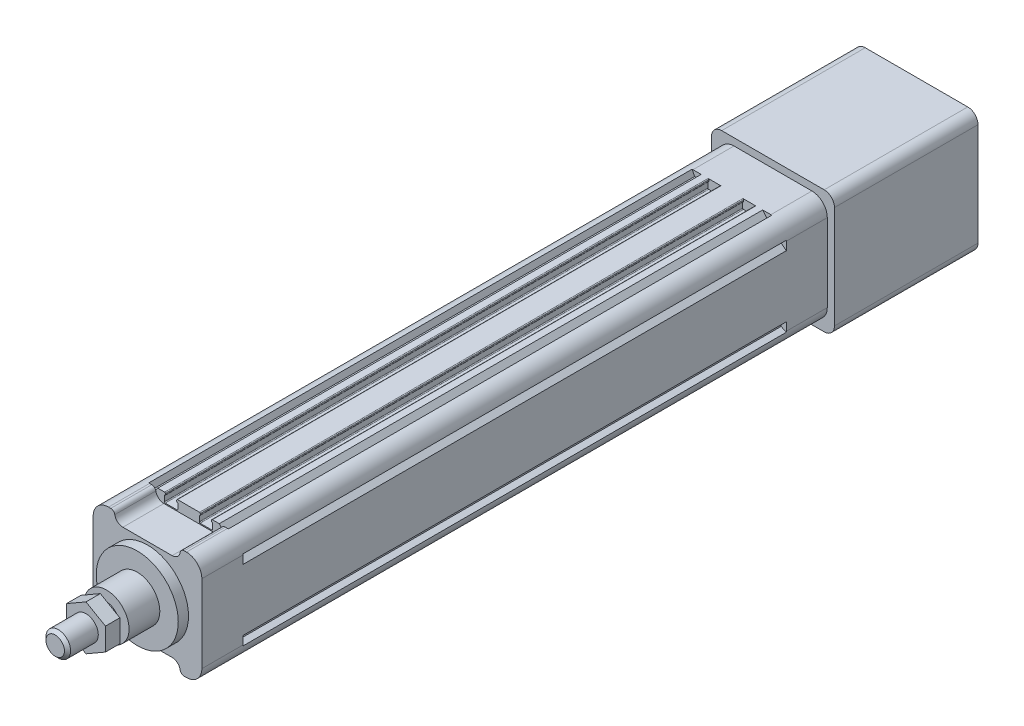
SolidWorks part; units mm, degrees
ref_plane "Front" through (0, 0, 0) normal (0, 0, 1) x (1, 0, 0)
ref_plane "Top" through (0, 0, 0) normal (0, 1, 0) x (1, 0, 0)
ref_plane "Right" through (0, 0, 0) normal (1, 0, 0) x (0, 0, -1)
sketch "草图1" plane through (0, 0, 0) normal (0, 0, 1) x (1, 0, 0)
  line L0 (19.7737, 3) -> (23.3, 3)
  line L1 (23.3, 3) -> (23.3, -3)
  line L2 (23.3, -3) -> (19.7737, -3)
  line L3 (-19.7737, -3) -> (-23.3, -3)
  line L4 (-23.3, -3) -> (-23.3, 3)
  line L5 (-23.3, 3) -> (-19.7737, 3)
  line L6 (-18.2, 24) -> (-19.4434, 26.4869)
  line L7 (-26.4869, 19.4434) -> (-24, 18.2)
  line L8 (-24, 18.2) -> (-24, 17.1)
  line L9 (-24, 17.1) -> (-26.5, 15)
  line L10 (-26.5, 15) -> (-26.5, -15)
  line L11 (-26.5, -15) -> (-24, -17.1)
  line L12 (-24, -17.1) -> (-24, -18.2)
  line L13 (-24, -18.2) -> (-26.4869, -19.4434)
  line L14 (-19.4434, -26.4869) -> (-18.2, -24)
  line L15 (-18.2, -24) -> (-17.1, -24)
  line L16 (-17.1, -24) -> (-15, -26.5)
  line L17 (-15, -26.5) -> (-11.65, -26.5)
  line L18 (-11.25, -26.1) -> (-11.25, -25.6)
  line L19 (-11.65, -25.2) -> (-11.75, -25.2)
  line L20 (-11.75, -25.2) -> (-11.75, -22.4)
  line L21 (-11.35, -22) -> (-5.65, -22)
  line L22 (-5.25, -22.4) -> (-5.25, -25.2)
  line L23 (-5.25, -25.2) -> (-5.35, -25.2)
  line L24 (-5.75, -25.6) -> (-5.75, -26.1)
  line L25 (-5.35, -26.5) -> (5.35, -26.5)
  line L26 (5.75, -26.1) -> (5.75, -25.6)
  line L27 (5.35, -25.2) -> (5.25, -25.2)
  line L28 (5.25, -25.2) -> (5.25, -22.4)
  line L29 (5.65, -22) -> (11.35, -22)
  line L30 (11.75, -22.4) -> (11.75, -25.2)
  line L31 (11.75, -25.2) -> (11.65, -25.2)
  line L32 (11.25, -25.6) -> (11.25, -26.1)
  line L33 (11.65, -26.5) -> (15, -26.5)
  line L34 (15, -26.5) -> (17.1, -24)
  line L35 (17.1, -24) -> (18.2, -24)
  line L36 (18.2, -24) -> (19.4434, -26.4869)
  line L37 (26.4869, -19.4434) -> (24, -18.2)
  line L38 (24, -18.2) -> (24, -17.1)
  line L39 (24, -17.1) -> (26.5, -15)
  line L40 (26.5, -15) -> (26.5, 15)
  line L41 (26.5, 15) -> (24, 17.1)
  line L42 (24, 17.1) -> (24, 18.2)
  line L43 (24, 18.2) -> (26.4869, 19.4434)
  line L44 (19.4434, 26.4869) -> (18.2, 24)
  line L45 (18.2, 24) -> (17.1, 24)
  line L46 (17.1, 24) -> (15, 26.5)
  line L47 (15, 26.5) -> (11.65, 26.5)
  line L48 (11.25, 26.1) -> (11.25, 25.6)
  line L49 (11.65, 25.2) -> (11.75, 25.2)
  line L50 (11.75, 25.2) -> (11.75, 22.4)
  line L51 (11.35, 22) -> (5.65, 22)
  line L52 (5.25, 22.4) -> (5.25, 25.2)
  line L53 (5.25, 25.2) -> (5.35, 25.2)
  line L54 (5.75, 25.6) -> (5.75, 26.1)
  line L55 (5.35, 26.5) -> (-5.35, 26.5)
  line L56 (-5.75, 26.1) -> (-5.75, 25.6)
  line L57 (-5.35, 25.2) -> (-5.25, 25.2)
  line L58 (-5.25, 25.2) -> (-5.25, 22.4)
  line L59 (-5.65, 22) -> (-11.35, 22)
  line L60 (-11.75, 22.4) -> (-11.75, 25.2)
  line L61 (-11.75, 25.2) -> (-11.65, 25.2)
  line L62 (-11.25, 25.6) -> (-11.25, 26.1)
  line L63 (-11.65, 26.5) -> (-15, 26.5)
  line L64 (-15, 26.5) -> (-17.1, 24)
  line L65 (-17.1, 24) -> (-18.2, 24)
  arc A0 (19.7737, 3) -> (-19.7737, 3) centre (0, 0) ccw
  arc A1 (-19.7737, -3) -> (19.7737, -3) centre (0, 0) ccw
  circle A2 centre (19, 19) radius 2.1
  circle A3 centre (19, -19) radius 2.1
  circle A4 centre (-19, -19) radius 2.1
  circle A5 centre (-19, 19) radius 2.1
  arc A6 (-19.4434, 26.4869) -> (-26.4869, 19.4434) centre (-19, 19) ccw
  arc A7 (-26.4869, -19.4434) -> (-19.4434, -26.4869) centre (-19, -19) ccw
  arc A8 (-11.65, -26.5) -> (-11.25, -26.1) centre (-11.65, -26.1) ccw
  arc A9 (-11.25, -25.6) -> (-11.65, -25.2) centre (-11.65, -25.6) ccw
  arc A10 (-11.35, -22) -> (-11.75, -22.4) centre (-11.35, -22.4) ccw
  arc A11 (-5.25, -22.4) -> (-5.65, -22) centre (-5.65, -22.4) ccw
  arc A12 (-5.35, -25.2) -> (-5.75, -25.6) centre (-5.35, -25.6) ccw
  arc A13 (-5.75, -26.1) -> (-5.35, -26.5) centre (-5.35, -26.1) ccw
  arc A14 (5.35, -26.5) -> (5.75, -26.1) centre (5.35, -26.1) ccw
  arc A15 (5.75, -25.6) -> (5.35, -25.2) centre (5.35, -25.6) ccw
  arc A16 (5.65, -22) -> (5.25, -22.4) centre (5.65, -22.4) ccw
  arc A17 (11.75, -22.4) -> (11.35, -22) centre (11.35, -22.4) ccw
  arc A18 (11.65, -25.2) -> (11.25, -25.6) centre (11.65, -25.6) ccw
  arc A19 (11.25, -26.1) -> (11.65, -26.5) centre (11.65, -26.1) ccw
  arc A20 (19.4434, -26.4869) -> (26.4869, -19.4434) centre (19, -19) ccw
  arc A21 (26.4869, 19.4434) -> (19.4434, 26.4869) centre (19, 19) ccw
  arc A22 (11.65, 26.5) -> (11.25, 26.1) centre (11.65, 26.1) ccw
  arc A23 (11.25, 25.6) -> (11.65, 25.2) centre (11.65, 25.6) ccw
  arc A24 (11.35, 22) -> (11.75, 22.4) centre (11.35, 22.4) ccw
  arc A25 (5.25, 22.4) -> (5.65, 22) centre (5.65, 22.4) ccw
  arc A26 (5.35, 25.2) -> (5.75, 25.6) centre (5.35, 25.6) ccw
  arc A27 (5.75, 26.1) -> (5.35, 26.5) centre (5.35, 26.1) ccw
  arc A28 (-5.35, 26.5) -> (-5.75, 26.1) centre (-5.35, 26.1) ccw
  arc A29 (-5.75, 25.6) -> (-5.35, 25.2) centre (-5.35, 25.6) ccw
  arc A30 (-5.65, 22) -> (-5.25, 22.4) centre (-5.65, 22.4) ccw
  arc A31 (-11.75, 22.4) -> (-11.35, 22) centre (-11.35, 22.4) ccw
  arc A32 (-11.65, 25.2) -> (-11.25, 25.6) centre (-11.65, 25.6) ccw
  arc A33 (-11.25, 26.1) -> (-11.65, 26.5) centre (-11.65, 26.1) ccw
extrude "凸台-拉伸1" add sketch "草图1" along normal blind 265
sketch "草图6" plane through (0, 0, 265) normal (0, 0, 1) x (1, 0, 0)
  line L0 (0, 0) -> (19, 0) construction
  line L2 (-26.5, -19) -> (-26.5, 19)
  line L3 (-19, 26.5) -> (-17.9161, 26.5)
  line L4 (26.5, -19) -> (26.5, 19)
  line L5 (-26.5, -26.5) -> (26.5, 26.5) construction
  line L6 (-26.5, 26.5) -> (26.5, -26.5) construction
  line L7 (-12, 21.5) -> (12, 21.5)
  line L9 (19, 26.5) -> (17.9161, 26.5)
  line L10 (19, -26.5) -> (17.9161, -26.5)
  line L11 (-12, -21.5) -> (12, -21.5)
  line L12 (-19, -26.5) -> (-17.9161, -26.5)
  arc A0 (12, 21.5) -> (15.9441, 24.8333) centre (12, 25.5) ccw
  arc A1 (-15.9441, 24.8333) -> (-12, 21.5) centre (-12, 25.5) ccw
  arc A2 (-15.9441, 24.8333) -> (-17.9161, 26.5) centre (-17.9161, 24.5) ccw
  arc A3 (15.9441, 24.8333) -> (17.9161, 26.5) centre (17.9161, 24.5) cw
  arc A4 (-26.5, -19) -> (-19, -26.5) centre (-19, -19) ccw
  arc A5 (19, -26.5) -> (26.5, -19) centre (19, -19) ccw
  arc A6 (26.5, 19) -> (19, 26.5) centre (19, 19) ccw
  arc A7 (-26.5, 19) -> (-19, 26.5) centre (-19, 19) cw
  arc A8 (15.9441, -24.8333) -> (17.9161, -26.5) centre (17.9161, -24.5) ccw
  arc A9 (12, -21.5) -> (15.9441, -24.8333) centre (12, -25.5) cw
  arc A10 (-15.9441, -24.8333) -> (-12, -21.5) centre (-12, -25.5) cw
  arc A11 (-15.9441, -24.8333) -> (-17.9161, -26.5) centre (-17.9161, -24.5) cw
  point P0 (0, 0)
  point P9 (0, 21.5)
  point P13 (20, 20.8461)
  point P16 (-12, 20.8461)
  dimension "D5" = 4
  dimension "D6" = 2
  dimension "D7" = 2
  dimension "D9" = 7.5
  dimension "D1" = 53
  dimension "D2" = 53
  dimension "D3" = 26.5
  dimension "D4" = 24
  dimension "D8" = 5
extrude "凸台-拉伸2" add sketch "草图6" along normal blind 20
sketch "草图7" plane through (0, 0, 285) normal (0, 0, 1) x (1, 0, 0)
  circle A0 centre (0, 0) radius 20
  dimension "D1" = 40
extrude "凸台-拉伸3" add sketch "草图7" along normal blind 5
sketch "草图9" plane through (0, 0, 290) normal (0, 0, 1) x (1, 0, 0)
  circle A0 centre (0, 0) radius 11
  dimension "D1" = 22
extrude "凸台-拉伸4" add sketch "草图9" along normal blind 15
sketch "草图10" plane through (0, 0, 305) normal (0, 0, 1) x (1, 0, 0)
  circle A0 centre (0, 0) radius 6
  dimension "D1" = 12
extrude "凸台-拉伸5" add sketch "草图10" along normal blind 25
sketch "草图11" plane through (0, 0, 0) normal (0, 0, -1) x (-1, 0, 0)
  line L1 (-19, -26.5) -> (19, -26.5)
  line L2 (-26.5, -19) -> (-26.5, 19)
  line L3 (-19, 26.5) -> (19, 26.5)
  line L4 (26.5, -19) -> (26.5, 19)
  line L5 (-26.5, -26.5) -> (26.5, 26.5) construction
  line L6 (-26.5, 26.5) -> (26.5, -26.5) construction
  arc A0 (-26.5, -19) -> (-19, -26.5) centre (-19, -19) ccw
  arc A1 (19, -26.5) -> (26.5, -19) centre (19, -19) ccw
  arc A2 (26.5, 19) -> (19, 26.5) centre (19, 19) ccw
  arc A3 (-26.5, 19) -> (-19, 26.5) centre (-19, 19) cw
  point P0 (0, 0)
  dimension "D3" = 7.5
  dimension "D1" = 53
  dimension "D2" = 53
extrude "凸台-拉伸6" add sketch "草图11" along normal blind 20
sketch "草图12" plane through (0, 0, -20) normal (0, 0, -1) x (-1, 0, 0)
  line L1 (-25, -30) -> (25, -30)
  line L2 (-30, -25) -> (-30, 25)
  line L3 (-25, 30) -> (25, 30)
  line L4 (30, -25) -> (30, 25)
  line L5 (-30, -30) -> (30, 30) construction
  line L6 (-30, 30) -> (30, -30) construction
  arc A0 (-30, -25) -> (-25, -30) centre (-25, -25) ccw
  arc A1 (25, -30) -> (30, -25) centre (25, -25) ccw
  arc A2 (30, 25) -> (25, 30) centre (25, 25) ccw
  arc A3 (-30, 25) -> (-25, 30) centre (-25, 25) cw
  point P0 (0, 0)
  dimension "D3" = 5
  dimension "D1" = 60
  dimension "D2" = 60
extrude "凸台-拉伸7" add sketch "草图12" along normal blind 70
sketch "草图14" plane through (0, 0, -90) normal (0, 0, -1) x (-1, 0, 0)
  circle A0 centre (0, 0) radius 19
  dimension "D1" = 38
extrude "切除-拉伸2" cut sketch "草图14" against normal blind 70
hole_wizard "M6 螺纹孔1" positions "草图15" profile "草图16" tap size "M6" standard "GB"
sketch "草图15" plane through (-26.5, 0, 0) normal (-1, 0, 0) x (0, 0, 1)
  line L0 (-20, -25) -> (-20, 25) construction
  line L1 (285, 19) -> (285, -19) construction
  point P0 (275, 11)
  point P2 (275, -11)
  point P4 (-10, 11)
  point P6 (-10, -11)
  dimension "D1" = 10
  dimension "D2" = 10
  dimension "D3" = 11
  dimension "D4" = 11
  dimension "D5" = 10
  dimension "D6" = 10
  dimension "D7" = 22
  dimension "D8" = 11
sketch "草图16" plane through (-26.5, 11, 275) normal (0, 1, 0) x (0, 0, 1)
  line L0 (0, 0) -> (0, 16.5022)
  line L1 (0, 16.5022) -> (2.5, 15)
  line L2 (2.5, 15) -> (2.5, 0)
  line L5 (2.5, 0) -> (0, 0)
  line L10 (0, 16.5022) -> (-2.5, 15) construction
  line L11 (0, -6.35) -> (0, 107.95) construction
  dimension "螺纹孔钻头直径" = 5
  dimension "螺纹孔钻头深度" = 15
  dimension "导头角度" = 118
cosmetic thread "孔螺蚊线4" parameters "D1"=12, "D2"=6
cosmetic thread "孔螺蚊线5" parameters "D1"=12, "D2"=6
cosmetic thread "孔螺蚊线6" parameters "D1"=12, "D2"=6
cosmetic thread "孔螺蚊线7" parameters "D1"=12, "D2"=6
chamfer "倒角1" distance 1.5 angle 45 1 edges at (6, 0, 330)
sketch "草图17" plane through (0, 0, 305) normal (0, 0, 1) x (1, 0, 0)
  line L1 (0, 10.9697) -> (-9.5, 5.4848)
  line L2 (-9.5, 5.4848) -> (-9.5, -5.4848)
  line L3 (-9.5, -5.4848) -> (0, -10.9697)
  line L4 (0, -10.9697) -> (9.5, -5.4848)
  line L5 (9.5, -5.4848) -> (9.5, 5.4848)
  line L6 (9.5, 5.4848) -> (0, 10.9697)
  circle A0 centre (0, 0) radius 9.5 construction
  dimension "D1" = 19
extrude "凸台-拉伸8" add sketch "草图17" along normal blind 7 from offset 3
